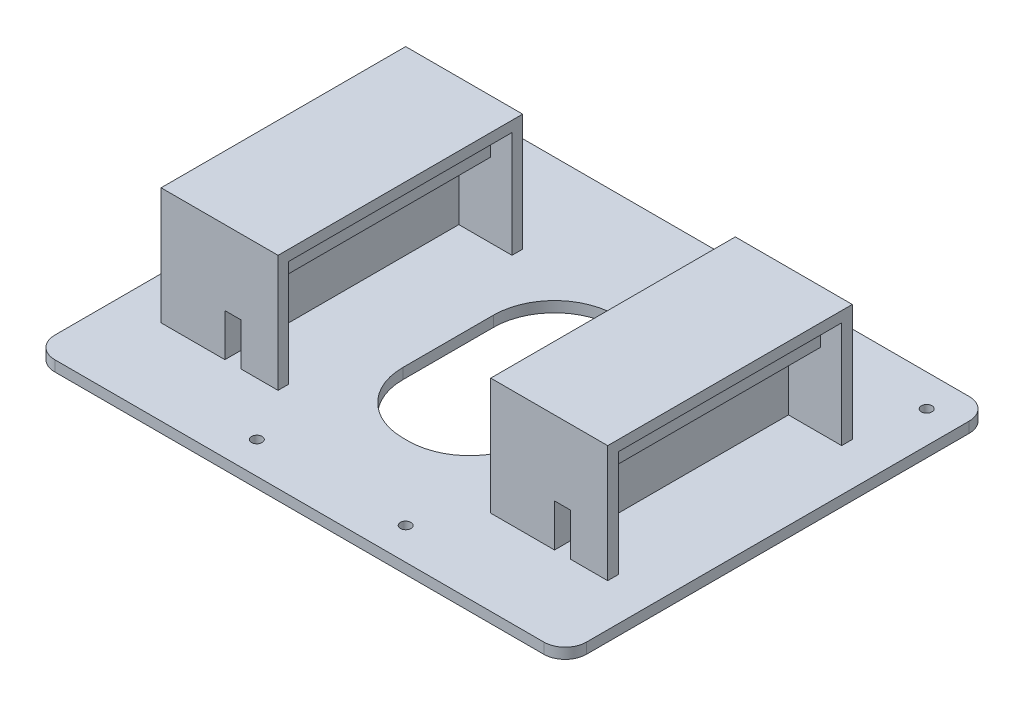
SolidWorks part; units mm, degrees
ref_plane "Plano frontal" through (0, 0, 0) normal (0, 0, 1) x (1, 0, 0)
ref_plane "Plano superior" through (0, 0, 0) normal (0, 1, 0) x (1, 0, 0)
ref_plane "Plano direito" through (0, 0, 0) normal (1, 0, 0) x (0, 0, -1)
sketch "Esboço1" plane through (0, 0, 0) normal (0, 1, 0) x (1, 0, 0)
  line L0 (-52.5, 100) -> (-52.5, 77.5) construction
  line L1 (140, -100) -> (-90, -100)
  line L2 (150, -90) -> (150, 90)
  line L3 (140, 100) -> (-90, 100)
  line L4 (-100, -90) -> (-100, 90)
  line L5 (150, -100) -> (-100, 100) construction
  line L6 (150, 100) -> (-100, -100) construction
  line L7 (-52.5, 77.5) -> (-100, 77.5) construction
  line L8 (102.5, -100) -> (102.5, -77.5) construction
  line L9 (102.5, -77.5) -> (150, -77.5) construction
  arc A0 (140, -100) -> (150, -90) centre (140, -90) ccw
  arc A1 (-90, -100) -> (-100, -90) centre (-90, -90) cw
  arc A2 (-90, 100) -> (-100, 90) centre (-90, 90) ccw
  arc A3 (150, 90) -> (140, 100) centre (140, 90) ccw
  dimension "D3" = 10
  dimension "D4" = 47.5
  dimension "D5" = 22.5
  dimension "D6" = 47.5
  dimension "D1" = 200
  dimension "D2" = 250
  dimension "D7" = 22.5
extrude "Ressalto-extrusão1" add sketch "Esboço1" along normal blind 5
sketch "Esboço2" plane through (0, 5, 0) normal (0, 1, 0) x (1, 0, 0)
  line L0 (60, -85) -> (-10, -85) construction
  line L1 (150, -90) -> (150, 90) construction
  line L2 (-100, 90) -> (-100, -90) construction
  line L3 (-10, -85) -> (-100, -85) construction
  line L4 (-90, -100) -> (140, -100) construction
  line L5 (140, 100) -> (-90, 100) construction
  circle A0 centre (-85, 85) radius 2.5
  circle A1 centre (-10, -85) radius 2.5
  circle A2 centre (60, -85) radius 2.5
  circle A4 centre (135, 85) radius 2.5
  dimension "D1" = 5
  dimension "D9" = 15
  dimension "D2" = 70
  dimension "D3" = 15
  dimension "D4" = 15
  dimension "D5" = 15
  dimension "D6" = 15
  dimension "D7" = 90
  dimension "D10" = 15
extrude "Corte-extrusão1" cut sketch "Esboço2" against normal blind 5
sketch "Esboço5" plane through (0, 5, 0) normal (0, 1, 0) x (1, 0, 0)
  line L0 (150, -60) -> (130, -60) construction
  line L1 (150, -90) -> (150, 90) construction
  line L2 (130, -60) -> (130, -100) construction
  line L3 (-90, -100) -> (140, -100) construction
  line L4 (125, -55) -> (105, -55)
  line L5 (130, -60) -> (75, -60)
  line L6 (130, -60) -> (130, -55)
  line L7 (130, 55) -> (75, 55)
  line L8 (75, -60) -> (75, -55)
  line L10 (125, 50) -> (105, 50)
  line L12 (130, -55) -> (125, -55)
  line L13 (125, 50) -> (130, 50)
  line L14 (80, -55) -> (75, -55)
  line L15 (80, 50) -> (75, 50)
  line L16 (75, 50) -> (75, 55)
  line L17 (80, -55) -> (80, 50) construction
  line L18 (75, -60) -> (75, 55) construction
  line L19 (130, 50) -> (130, 55)
  line L20 (130, -60) -> (130, 55) construction
  line L21 (125, -55) -> (125, 50) construction
  line L22 (100, -55) -> (80, -55)
  line L23 (105, -55) -> (105, 50)
  line L24 (100, -55) -> (100, 50)
  line L25 (125, -55) -> (80, -55) construction
  line L26 (100, 50) -> (80, 50)
  line L27 (125, 50) -> (80, 50) construction
  line L30 (-50, -55) -> (-50, 50)
  line L31 (-55, -55) -> (-55, 50)
  line L32 (-50, -55) -> (-30, -55)
  line L33 (-80, 50) -> (-80, 55)
  line L34 (-25, 50) -> (-25, 55)
  line L35 (-30, 50) -> (-25, 50)
  line L36 (-30, -55) -> (-25, -55)
  line L37 (-75, 50) -> (-80, 50)
  line L38 (-80, -55) -> (-75, -55)
  line L39 (-75, 50) -> (-55, 50)
  line L40 (-25, -60) -> (-25, -55)
  line L41 (-80, 55) -> (-25, 55)
  line L42 (-80, -60) -> (-80, -55)
  line L43 (-80, -60) -> (-25, -60)
  line L44 (-75, -55) -> (-55, -55)
  line L45 (-30, 50) -> (-50, 50)
  dimension "D1" = 40
  dimension "D2" = 20
  dimension "D3" = 55
  dimension "D4" = 5
extrude "Ressalto-extrusão3" add sketch "Esboço5" along normal blind 35
sketch "Esboço6" plane through (0, 5, 0) normal (0, 1, 0) x (1, 0, 0)
  line L0 (-90, -100) -> (140, -100) construction
  line L1 (23.7183, 50) -> (26.2817, 50)
  line L2 (-5, 21.2817) -> (-5, -21.2817)
  line L3 (23.7183, -50) -> (26.2817, -50)
  line L4 (55, 21.2817) -> (55, -21.2817)
  line L5 (150, -90) -> (150, 90) construction
  arc A0 (-5, 21.2817) -> (23.7183, 50) centre (23.7183, 21.2817) cw
  arc A1 (26.2817, 50) -> (55, 21.2817) centre (26.2817, 21.2817) cw
  arc A2 (23.7183, -50) -> (-5, -21.2817) centre (23.7183, -21.2817) cw
  arc A3 (26.2817, -50) -> (55, -21.2817) centre (26.2817, -21.2817) ccw
  point P10 (-5, 50)
  point P13 (55, 50)
  point P16 (-5, -50)
  dimension "D5" = 28.7183
  dimension "D1" = 50
  dimension "D2" = 100
  dimension "D3" = 95
  dimension "D4" = 60
extrude "Corte-extrusão2" cut sketch "Esboço6" against normal blind 10
sketch "Esboço7" plane through (0, 40, 0) normal (0, 1, 0) x (1, 0, 0)
  line L1 (130, -60) -> (75, -60)
  line L2 (130, -60) -> (130, -55)
  line L3 (130, -55) -> (75, -55)
  line L4 (75, -60) -> (75, -55)
  line L5 (75, 55) -> (130, 55)
  line L6 (75, 55) -> (75, 50)
  line L7 (75, 50) -> (130, 50)
  line L8 (130, 55) -> (130, 50)
  line L9 (-25, 50) -> (-80, 50)
  line L10 (-25, 50) -> (-25, 55)
  line L11 (-25, 55) -> (-80, 55)
  line L12 (-80, 50) -> (-80, 55)
  line L13 (-80, -55) -> (-25, -55)
  line L14 (-80, -55) -> (-80, -60)
  line L15 (-80, -60) -> (-25, -60)
  line L16 (-25, -55) -> (-25, -60)
extrude "Ressalto-extrusão4" add sketch "Esboço7" along normal blind 20
sketch "Esboço8" plane through (0, 0, -50) normal (0, 0, 1) x (1, 0, 0)
  line L0 (130, 60) -> (130, 5) construction
  line L1 (75, 60) -> (130, 60)
  line L2 (75, 60) -> (75, 55)
  line L3 (75, 55) -> (130, 55)
  line L4 (130, 60) -> (130, 55)
  line L5 (-25, 60) -> (-25, 5) construction
  line L6 (-80, 60) -> (-25, 60)
  line L7 (-80, 60) -> (-80, 55)
  line L8 (-80, 55) -> (-25, 55)
  line L9 (-25, 60) -> (-25, 55)
  line L10 (105, 40) -> (130, 40) construction
  line L11 (130, 40) -> (75, 40) construction
  line L12 (75, 60) -> (75, 5) construction
  line L13 (-80, 60) -> (-80, 5) construction
  line L14 (75, 40) -> (130, 40)
  line L15 (75, 40) -> (75, 45.0003)
  line L16 (75, 45.0003) -> (130, 45.0003)
  line L17 (130, 40) -> (130, 45.0003)
  line L18 (-80, 40) -> (-25, 40)
  line L19 (-80, 40) -> (-80, 45.0003)
  line L20 (-80, 45.0003) -> (-25, 45.0003)
  line L21 (-25, 40) -> (-25, 45.0003)
  dimension "D1" = 5
  dimension "D2" = 5
extrude "Ressalto-extrusão6" add sketch "Esboço8" along normal blind 105
sketch "Esboço9" plane through (0, 0, -55) normal (0, 0, -1) x (-1, 0, 0)
  line L0 (80, 5) -> (55, 5) construction
  line L2 (-75, 5) -> (-100, 5) construction
  line L4 (-100, 5) -> (-100, 25) construction
  line L5 (-100, 25) -> (-92.5, 25) construction
  line L6 (-92.5, 25) -> (-92.5, 5) construction
  line L8 (-100, 25) -> (-92.5, 25)
  line L9 (-100, 25) -> (-100, 5)
  line L10 (-100, 5) -> (-92.5, 5)
  line L11 (-92.5, 25) -> (-92.5, 5)
  line L12 (55, 5) -> (62.5, 5)
  line L13 (55, 5) -> (55, 25)
  line L14 (55, 25) -> (62.5, 25)
  line L15 (62.5, 5) -> (62.5, 25)
  dimension "D1" = 7.5
  dimension "D2" = 20
  dimension "D3" = 20
  dimension "D4" = 7.5
extrude "Corte-extrusão4" cut sketch "Esboço9" against normal blind 5
sketch "Esboço10" plane through (0, 0, 60) normal (0, 0, 1) x (1, 0, 0)
  line L0 (130, 5) -> (105, 5) construction
  line L1 (75, 5) -> (130, 5) construction
  line L2 (105, 5) -> (105, 25) construction
  line L3 (105, 25) -> (112.5, 25) construction
  line L4 (112.5, 25) -> (112.5, 5) construction
  line L5 (-25, 5) -> (-50, 5) construction
  line L6 (-80, 5) -> (-25, 5) construction
  line L7 (-25, 60) -> (-25, 5) construction
  line L8 (-50, 5) -> (-50, 25) construction
  line L9 (-50, 25) -> (-42.5, 25) construction
  line L10 (-42.5, 25) -> (-42.5, 5) construction
  line L12 (-50, 25) -> (-42.5, 25)
  line L13 (-50, 25) -> (-50, 5)
  line L14 (-50, 5) -> (-42.5, 5)
  line L15 (-42.5, 25) -> (-42.5, 5)
  line L16 (105, 25) -> (112.5, 25)
  line L17 (105, 25) -> (105, 5)
  line L18 (105, 5) -> (112.5, 5)
  line L19 (112.5, 25) -> (112.5, 5)
extrude "Corte-extrusão5" cut sketch "Esboço10" against normal blind 5
sketch "Esboço11" plane through (130, 0, 0) normal (1, 0, 0) x (0, 0, -1)
  line L1 (-55, 45.0003) -> (50, 45.0003)
  line L2 (-55, 45.0003) -> (-55, 40)
  line L3 (-55, 40) -> (50, 40)
  line L4 (50, 45.0003) -> (50, 40)
extrude "Corte-extrusão6" cut sketch "Esboço11" against normal blind 10
sketch "Esboço12" plane through (75, 0, 0) normal (-1, 0, 0) x (0, 0, 1)
  line L1 (-50, 45.0003) -> (55, 45.0003)
  line L2 (-50, 45.0003) -> (-50, 40)
  line L3 (-50, 40) -> (55, 40)
  line L4 (55, 45.0003) -> (55, 40)
extrude "Corte-extrusão7" cut sketch "Esboço12" against normal blind 10
sketch "Esboço13" plane through (-25, 0, 0) normal (1, 0, 0) x (0, 0, -1)
  line L1 (-55, 45.0003) -> (50, 45.0003)
  line L2 (-55, 45.0003) -> (-55, 40)
  line L3 (-55, 40) -> (50, 40)
  line L4 (50, 45.0003) -> (50, 40)
extrude "Corte-extrusão8" cut sketch "Esboço13" against normal blind 10
sketch "Esboço14" plane through (-80, 0, 0) normal (-1, 0, 0) x (0, 0, 1)
  line L1 (-50, 45.0003) -> (55, 45.0003)
  line L2 (-50, 45.0003) -> (-50, 40)
  line L3 (-50, 40) -> (55, 40)
  line L4 (55, 45.0003) -> (55, 40)
extrude "Corte-extrusão9" cut sketch "Esboço14" against normal blind 10
